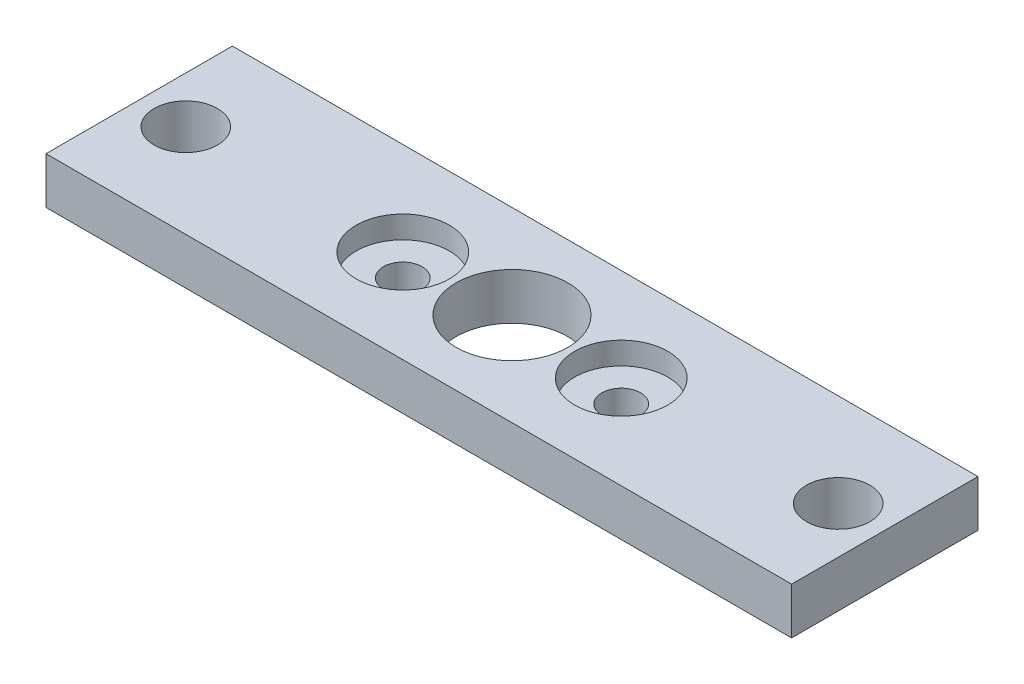
SolidWorks part; units mm, degrees
ref_plane "Front Plane" through (0, 0, 0) normal (0, 0, 1) x (1, 0, 0)
ref_plane "Top Plane" through (0, 0, 0) normal (0, 1, 0) x (1, 0, 0)
ref_plane "Right Plane" through (0, 0, 0) normal (1, 0, 0) x (0, 0, -1)
sketch "Sketch1" plane through (0, 0, 0) normal (0, 1, 0) x (1, 0, 0)
  line L0 (-7.4422, 0) -> (7.4422, 0) construction
  line L1 (22.225, 0) -> (-22.225, 0) construction
  line L2 (-25.4, -6.35) -> (25.4, -6.35)
  line L3 (-25.4, -6.35) -> (-25.4, 6.35)
  line L4 (-25.4, 6.35) -> (25.4, 6.35)
  line L5 (25.4, -6.35) -> (25.4, 6.35)
  line L6 (-25.4, -6.35) -> (25.4, 6.35) construction
  line L7 (-25.4, 6.35) -> (25.4, -6.35) construction
  circle A0 centre (0, 0) radius 3.81
  circle A1 centre (7.4422, 0) radius 1.3208
  circle A2 centre (-7.4422, 0) radius 1.3208
  circle A3 centre (-22.225, 0) radius 2.159
  circle A4 centre (22.225, 0) radius 2.159
  point P7 (0, 0)
  point P8 (0, 0)
  point P17 (0, 0)
  dimension "D2" = 2.6416
  dimension "D3" = 7.62
  dimension "D6" = 4.318
  dimension "D1" = 14.8844
  dimension "D4" = 50.8
  dimension "D5" = 12.7
  dimension "D7" = 44.45
extrude "Boss-Extrude1" add sketch "Sketch1" along normal blind 3.175
sketch "Sketch2" plane through (0, 3.175, 0) normal (0, 1, 0) x (1, 0, 0)
  circle A0 centre (-7.4422, 0) radius 3.175
  circle A1 centre (7.4422, 0) radius 3.175
  dimension "D1" = 6.35
extrude "Cut-Extrude1" cut sketch "Sketch2" against normal blind 1.524
